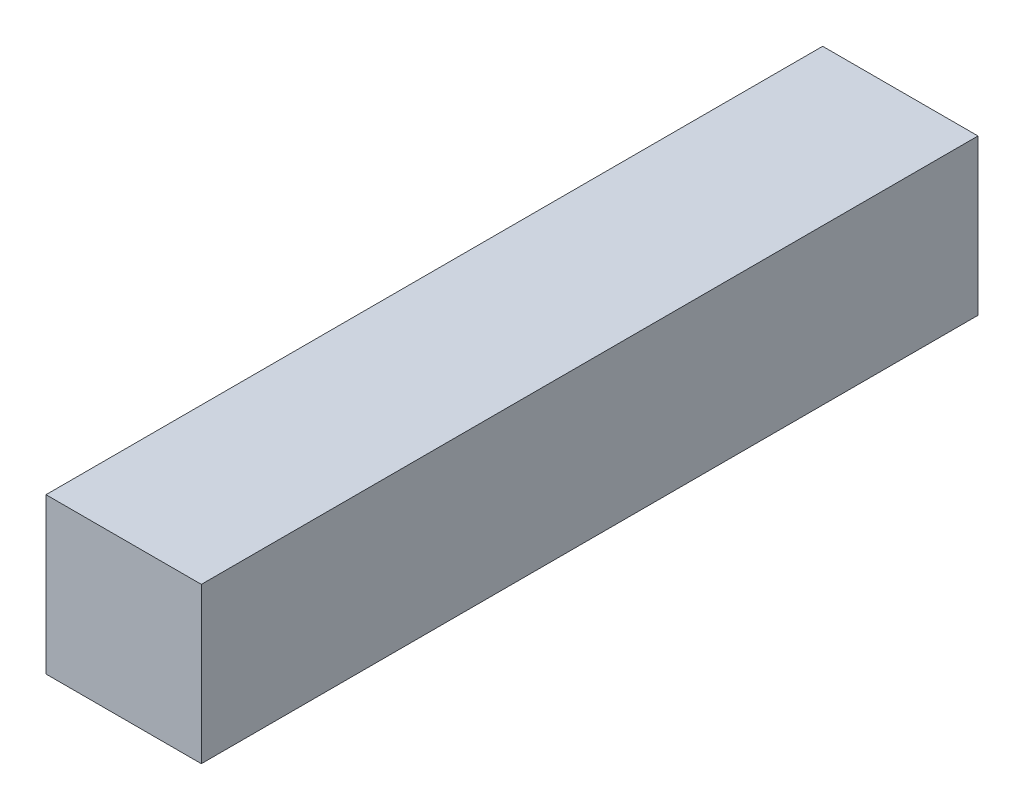
SolidWorks part; units mm, degrees
material "Plain Carbon Steel"
ref_plane "Front Plane" through (0, 0, 0) normal (1, 0, 0) x (0, 1, 0)
ref_plane "Top Plane" through (0, 0, 0) normal (0, 0, 1) x (0, 1, 0)
ref_plane "Right Plane" through (0, 0, 0) normal (0, 1, 0) x (-1, 0, 0)
sketch "Sketch1" plane through (0, 0, 0) normal (0, 0, 1) x (0, 1, 0)
  line L1 (2, 2) -> (-2, 2)
  line L2 (2, 2) -> (2, -2)
  line L3 (2, -2) -> (-2, -2)
  line L4 (-2, 2) -> (-2, -2)
  line L5 (2, 2) -> (-2, -2) construction
  line L6 (2, -2) -> (-2, 2) construction
  point P0 (0, 0)
  dimension "D1" = 4
  dimension "D2" = 4
extrude "Boss-Extrude1" add sketch "Sketch1" along normal blind 20
